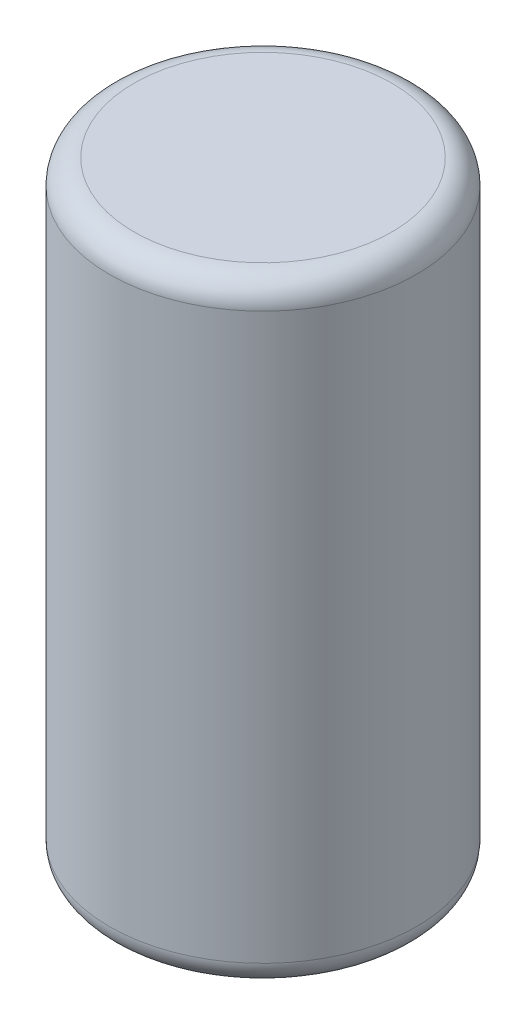
SolidWorks part; units mm, degrees
material "Plain Carbon Steel"
ref_plane "Front Plane" through (0, 0, 0) normal (0, 0, 1) x (1, 0, 0)
ref_plane "Top Plane" through (0, 0, 0) normal (0, 1, 0) x (1, 0, 0)
ref_plane "Right Plane" through (0, 0, 0) normal (1, 0, 0) x (0, 0, -1)
sketch "Sketch2" plane through (0, 0, 0) normal (1, 0, 0) x (0, 0, -1)
  line L0 (0, 4.2507) -> (0, -4.5223) construction
  line L1 (0, -3.175) -> (0, 3.175)
  line L2 (0, -3.175) -> (1.5875, -3.175)
  line L3 (0, 3.175) -> (1.5875, 3.175)
  line L4 (1.5875, -3.175) -> (1.5875, 3.175)
  dimension "D1" = 3.175
  dimension "D2" = 6.35
revolve "Revolve1" add sketch "Sketch2" angle 360 about L0
fillet "Fillet1" radius 0.254 2 edges at (0, -3.175, 1.5875) (0, 3.175, 1.5875)
